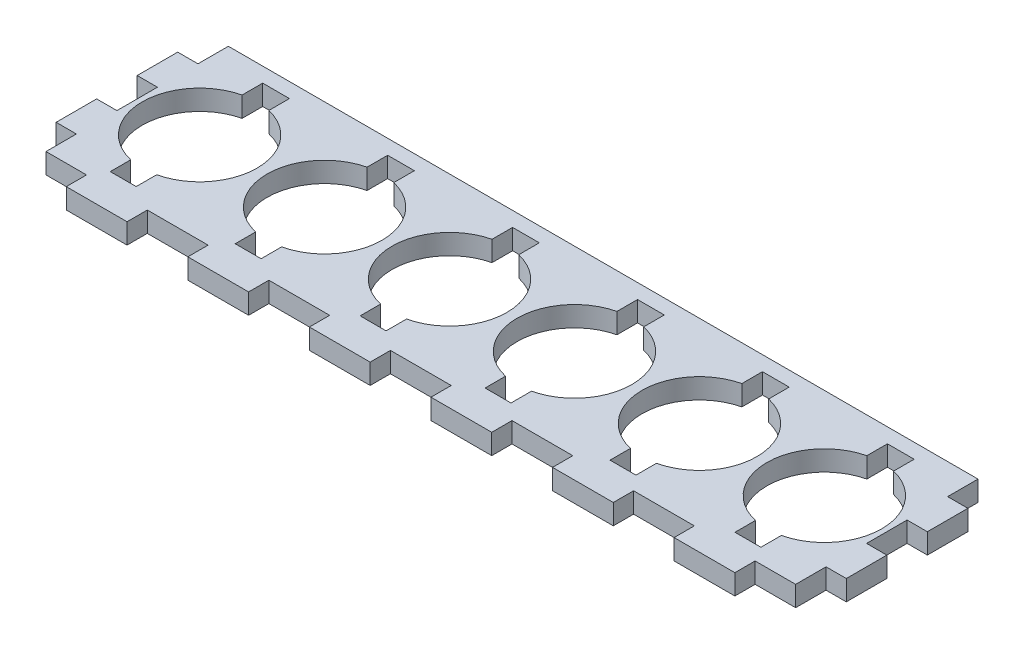
SolidWorks part; units mm, degrees
material "Pin"
ref_plane "Front" through (0, 0, 0) normal (0, 0, 1) x (1, 0, 0)
ref_plane "Top" through (0, 0, 0) normal (0, 1, 0) x (1, 0, 0)
ref_plane "Right" through (0, 0, 0) normal (1, 0, 0) x (0, 0, -1)
sketch "Esquisse1" plane through (0, 0, 0) normal (0, 1, 0) x (1, 0, 0)
  line L1 (-117.475, 28.575) -> (117.475, 28.575)
  line L2 (-117.475, 28.575) -> (-117.475, -28.575)
  line L3 (-117.475, -28.575) -> (117.475, -28.575)
  line L4 (117.475, 28.575) -> (117.475, -28.575)
  line L5 (-117.475, 28.575) -> (117.475, -28.575) construction
  line L6 (-117.475, -28.575) -> (117.475, 28.575) construction
  point P0 (0, 0)
  dimension "D1" = 234.95
  dimension "D2" = 57.15
extrude "Boss.-Extru.1" add sketch "Esquisse1" along normal blind 6.35
sketch "Esquisse2" plane through (0, 6.35, 0) normal (0, 1, 0) x (1, 0, 0)
  line L0 (117.475, -28.575) -> (117.475, 28.575) construction
  line L1 (97.8958, -23.9531) -> (97.8958, 23.9531) construction
  line L4 (93.7048, 17.5053) -> (93.7048, 23.9531)
  line L5 (93.7048, 23.9531) -> (102.0868, 23.9531)
  line L6 (102.0868, 17.5053) -> (102.0868, 23.9531)
  line L10 (93.8318, -17.5352) -> (93.8318, -23.9531)
  line L11 (93.8318, -23.9531) -> (101.9598, -23.9531)
  line L12 (101.9598, -17.5352) -> (101.9598, -23.9531)
  arc A0 (101.9598, -17.5352) -> (102.0868, 17.5053) centre (97.8958, 0) ccw
  arc A1 (93.7048, 17.5053) -> (93.8318, -17.5352) centre (97.8958, 0) ccw
  point P2 (97.8958, 0)
  point P5 (97.8958, 18)
  point P10 (97.8958, 23.9531)
  point P12 (97.8958, -23.9531)
  point P13 (97.8958, -18)
  dimension "D1" = 36
  dimension "D2" = 19.5792
  dimension "D3" = 47.9062
  dimension "D4" = 8.382
  dimension "D5" = 8.128
extrude "Enlèv. mat.-Extru.1" cut sketch "Esquisse2" against normal blind 6.35
pattern_linear "Répétition linéaire1" count 6 spacing 39.1583 along (-1, 0, 0) of "Enlèv. mat.-Extru.1"
sketch "Esquisse3" plane through (0, 6.35, 0) normal (0, 1, 0) x (1, 0, 0)
  line L0 (-117.475, -28.575) -> (117.475, -28.575) construction
  line L1 (-104.775, -28.575) -> (-85.725, -28.575)
  line L2 (-104.775, -28.575) -> (-104.775, -34.925)
  line L3 (-104.775, -34.925) -> (-85.725, -34.925)
  line L4 (-85.725, -28.575) -> (-85.725, -34.925)
  line L5 (-117.475, 28.575) -> (-117.475, -28.575) construction
  dimension "D1" = 19.05
  dimension "D2" = 6.35
  dimension "D3" = 12.7
extrude "Boss.-Extru.2" add sketch "Esquisse3" against normal blind 6.35
pattern_linear "Répétition linéaire2" count 6 spacing 38.1 along (1, 0, 0) of "Boss.-Extru.2"
sketch "Esquisse5" plane through (0, 6.35, 0) normal (0, 1, 0) x (1, 0, 0)
  line L0 (-117.475, 28.575) -> (-117.475, -28.575) construction
  line L1 (-117.475, -19.05) -> (-123.825, -19.05)
  line L2 (-117.475, -19.05) -> (-117.475, -6.35)
  line L3 (-117.475, -6.35) -> (-123.825, -6.35)
  line L4 (-123.825, -19.05) -> (-123.825, -6.35)
  line L5 (-117.475, -28.575) -> (-104.775, -28.575) construction
  dimension "D1" = 9.525
  dimension "D2" = 6.35
  dimension "D3" = 12.7
extrude "Boss.-Extru.4" add sketch "Esquisse5" against normal blind 6.35
pattern_linear "Répétition linéaire4" count 2 spacing 25.4 along (0, 0, -1) count 2 spacing 241.3 along (1, 0, 0) of "Boss.-Extru.4"
